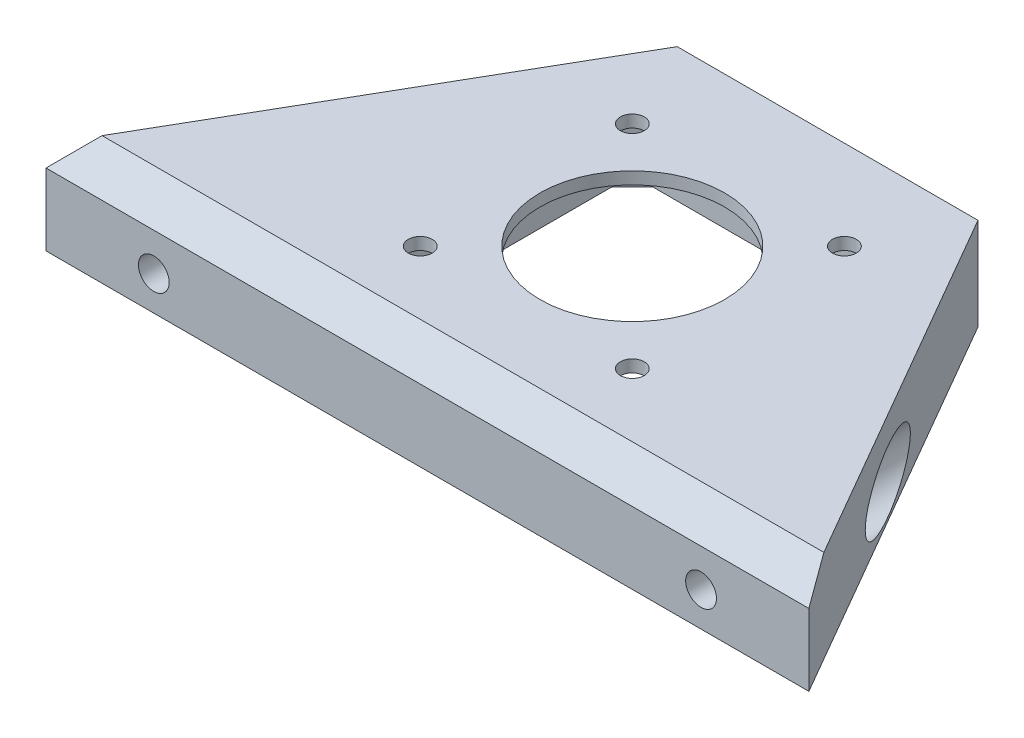
SolidWorks part; units mm, degrees
ref_plane "Front" through (0, 0, 0) normal (0, 0, 1) x (1, 0, 0)
ref_plane "Top" through (0, 0, 0) normal (0, 1, 0) x (1, 0, 0)
ref_plane "Right" through (0, 0, 0) normal (1, 0, 0) x (0, 0, -1)
sketch "Sketch1" plane through (0, 0, 0) normal (0, 1, 0) x (1, 0, 0)
  line L0 (-56.625, 0) -> (56.625, 0)
  line L1 (56.625, 0) -> (21.984, 60)
  line L2 (21.984, 60) -> (-21.984, 60)
  line L3 (-21.984, 60) -> (-56.625, 0)
  point P2 (0, 0)
  point P5 (0, 60)
  dimension "D1" = 60
  dimension "D2" = 113.25
  dimension "D3" = 60
extrude "Boss-Extrude1" add sketch "Sketch1" along normal blind 13.5
sketch "Sketch2" plane through (0, 0, 0) normal (0, -1, 0) x (1, 0, 0)
  line L0 (-56.625, 0) -> (56.625, 0) construction
  line L1 (22.5, -53.95) -> (-22.5, -53.95)
  line L2 (22.5, -53.95) -> (22.5, -8.95)
  line L3 (22.5, -8.95) -> (-22.5, -8.95)
  line L4 (-22.5, -53.95) -> (-22.5, -8.95)
  point P4 (0, -8.95)
  point P7 (-22.5, -31.45)
  dimension "D1" = 45
  dimension "D2" = 31.45
extrude "Cut-Extrude1" cut sketch "Sketch2" against normal offset from surface (11.72 mm away) 1.78 up to face at (0, 13.5, -30)
sketch "Sketch3" plane through (0, 11.72, 0) normal (0, -1, 0) x (1, 0, 0)
  line L0 (22.5, -53.95) -> (22.5, -8.95) construction
  line L1 (-22.5, -53.95) -> (22.5, -53.95) construction
  circle A0 centre (0, -31.45) radius 13.5
  point P5 (22.5, -31.45)
  point P9 (0, -53.95)
  dimension "D1" = 27
extrude "Cut-Extrude2" cut sketch "Sketch3" against normal through all
chamfer "Chamfer1" distance 3 angle 45 4 edges at (22.5, 5.86, -53.95) (22.5, 5.86, -8.95) (-22.5, 5.86, -8.95) (-22.5, 5.86, -53.95)
sketch "Sketch5" plane through (0, 13.5, 0) normal (0, 1, 0) x (1, 0, 0)
  line L0 (-15.5, 46.95) -> (15.5, 15.95) construction
  line L1 (-15.5, 15.95) -> (15.5, 46.95) construction
  line L2 (0, 44.95) -> (0, 17.95) construction
  circle A0 centre (15.5, 46.95) radius 1.75
  circle A1 centre (15.5, 15.95) radius 1.75
  circle A2 centre (-15.5, 15.95) radius 1.75
  circle A3 centre (-15.5, 46.95) radius 1.75
  circle A4 centre (0, 31.45) radius 13.5 construction
  point P8 (0, 31.45)
  point P10 (0, 31.45)
  point P11 (0, 31.45)
  dimension "D2" = 3.5
  dimension "D1" = 31
sketch "Sketch7" plane through (0, 13.5, 0) normal (0, 1, 0) x (1, 0, 0)
  line L1 (-56.625, 0) -> (56.625, 0)
  line L2 (-56.625, 0) -> (-56.625, 1.5)
  line L3 (-56.625, 1.5) -> (56.625, 1.5)
  line L4 (56.625, 0) -> (56.625, 1.5)
  dimension "D1" = 1.5
extrude "Cut-Extrude4" cut sketch "Sketch7" against normal through all
chamfer "Chamfer2" distance 3 angle 60 1 edges at (0, 13.5, -1.5)
sketch "Sketch8" plane through (0, 0, -1.5) normal (0, 0, 1) x (1, 0, 0)
  line L0 (-40, 5) -> (40, 5) construction
  line L1 (55.759, 0) -> (-55.759, 0) construction
  circle A0 centre (-40, 5) radius 2.25
  circle A1 centre (40, 5) radius 2.25
  point P4 (0, 5)
  dimension "D2" = 4.5
  dimension "D1" = 80
  dimension "D3" = 5
extrude "Cut-Extrude5" cut sketch "Sketch8" against normal through all
sketch "Sketch9" plane through (0, 0, -1.5) normal (0, 0, 1) x (1, 0, 0)
  circle A0 centre (-40, 5) radius 4.5
  circle A1 centre (40, 5) radius 4.5
  dimension "D1" = 9
extrude "Cut-Extrude6" cut sketch "Sketch9" against normal through all from offset 4 offset against normal yes
extrude "Cut-Extrude7" cut sketch "Sketch5" against normal through all
